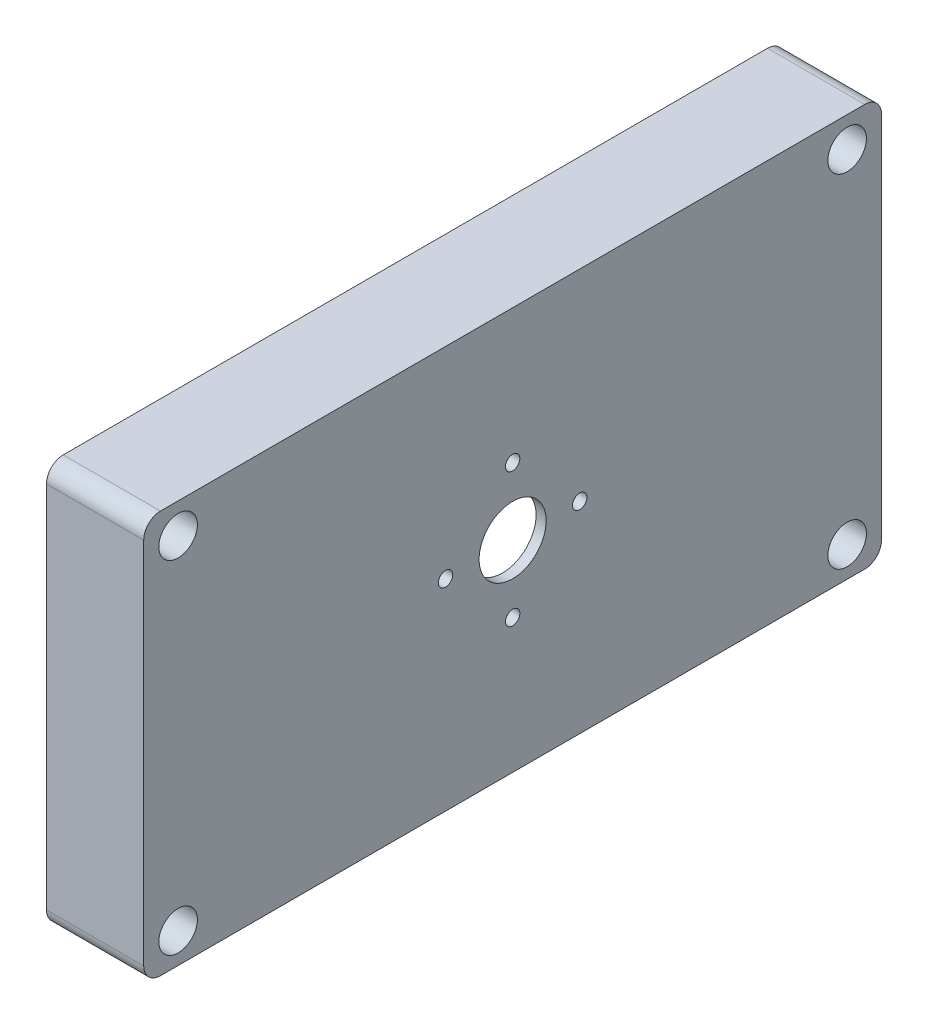
SolidWorks part; units mm, degrees
material "ألمنيوم خلائطي"
ref_plane "Front" through (0, 0, 0) normal (0, 0, 1) x (1, 0, 0)
ref_plane "Top" through (0, 0, 0) normal (0, 1, 0) x (1, 0, 0)
ref_plane "Right" through (0, 0, 0) normal (1, 0, 0) x (0, 0, -1)
sketch "Sketch1" plane through (0, 0, 0) normal (1, 0, 0) x (0, 0, -1)
  line L1 (110, 60) -> (-110, 60)
  line L2 (110, 60) -> (110, -60)
  line L3 (110, -60) -> (-110, -60)
  line L4 (-110, 60) -> (-110, -60)
  line L5 (110, 60) -> (-110, -60) construction
  line L6 (110, -60) -> (-110, 60) construction
  point P0 (0, 0)
  dimension "D1" = 120
  dimension "D2" = 220
extrude "Boss-Extrude1" add sketch "Sketch1" along normal mid plane 29
sketch "Sketch2" plane through (-14.5, 0, 0) normal (-1, 0, 0) x (0, 0, 1)
  line L0 (-87.25, 53.4) -> (87.25, 53.4)
  line L1 (87.25, 53.4) -> (87.25, 35.9)
  line L2 (87.25, 35.9) -> (103.4, 18.75)
  line L3 (103.4, 18.75) -> (103.4, -18.75)
  line L4 (-103.4, 18.75) -> (-103.4, -18.75)
  line L5 (-87.25, 35.9) -> (-103.4, 18.75)
  line L6 (-87.25, 53.4) -> (-87.25, 35.9)
  line L7 (87.25, -35.9) -> (103.4, -18.75)
  line L8 (87.25, -53.4) -> (87.25, -35.9)
  line L9 (-87.25, -53.4) -> (87.25, -53.4)
  line L10 (-87.25, -53.4) -> (-87.25, -35.9)
  line L11 (-87.25, -35.9) -> (-103.4, -18.75)
  line L12 (0, 0) -> (0, 60) construction
  line L13 (-110, 60) -> (110, 60) construction
  line L14 (0, 0) -> (110, 0) construction
  line L15 (110, 60) -> (110, -60) construction
  point P10 (0, 53.4)
  point P11 (103.4, 0)
  point P23 (-103.4, 0)
  dimension "D1" = 87.25
  dimension "D2" = 17.5
  dimension "D3" = 6.6
  dimension "D4" = 18.75
  dimension "D5" = 6.6
extrude "Cut-Extrude1" cut sketch "Sketch2" against normal blind 26
fillet "Fillet1" radius 1 8 edges at (-1.5, 18.75, -103.4) (-1.5, -18.75, -103.4) (-1.5, -53.4, -87.25) (-1.5, -53.4, 87.25) (-1.5, -18.75, 103.4) (-1.5, 18.75, 103.4) (-1.5, 53.4, 87.25) (-1.5, 53.4, -87.25)
fillet "Fillet2" radius 10 4 edges at (-1.5, -35.9, -87.25) (-1.5, -35.9, 87.25) (-1.5, 35.9, 87.25) (-1.5, 35.9, -87.25)
sketch "Sketch3" plane through (-14.5, 0, 0) normal (-1, 0, 0) x (0, 0, 1)
  line L24 (-89.25, 52.4) -> (-89.25, 39.8674)
  line L25 (-91.4259, 34.3828) -> (-104.584, 20.41)
  line L26 (-105.4, 18.3533) -> (-105.4, -18.3533)
  line L27 (-104.584, -20.41) -> (-91.4259, -34.3828)
  line L28 (-89.25, -39.8674) -> (-89.25, -52.4)
  line L29 (-86.25, -55.4) -> (86.25, -55.4)
  line L30 (89.25, -52.4) -> (89.25, -39.8674)
  line L31 (91.4259, -34.3828) -> (104.584, -20.41)
  line L32 (105.4, -18.3533) -> (105.4, 18.3533)
  line L33 (104.584, 20.41) -> (91.4259, 34.3828)
  line L34 (89.25, 39.8674) -> (89.25, 52.4)
  line L35 (86.25, 55.4) -> (-86.25, 55.4)
  line L36 (-89.25, 52.4) -> (-89.25, 39.8674)
  line L37 (-91.4259, 34.3828) -> (-104.584, 20.41)
  line L38 (-105.4, 18.3533) -> (-105.4, -18.3533)
  line L39 (-104.584, -20.41) -> (-91.4259, -34.3828)
  line L40 (-89.25, -39.8674) -> (-89.25, -52.4)
  line L41 (-86.25, -55.4) -> (86.25, -55.4)
  line L42 (89.25, -52.4) -> (89.25, -39.8674)
  line L43 (91.4259, -34.3828) -> (104.584, -20.41)
  line L44 (105.4, -18.3533) -> (105.4, 18.3533)
  line L45 (104.584, 20.41) -> (91.4259, 34.3828)
  line L46 (89.25, 39.8674) -> (89.25, 52.4)
  line L47 (86.25, 55.4) -> (-86.25, 55.4)
  line L48 (-87.25, 52.4) -> (-87.25, 39.8674)
  line L49 (-89.9699, 33.0117) -> (-103.128, 19.0388)
  line L50 (-103.4, 18.3533) -> (-103.4, -18.3533)
  line L51 (-103.128, -19.0388) -> (-89.9699, -33.0117)
  line L52 (-87.25, -39.8674) -> (-87.25, -52.4)
  line L53 (-86.25, -53.4) -> (86.25, -53.4)
  line L54 (87.25, -52.4) -> (87.25, -39.8674)
  line L55 (89.9699, -33.0117) -> (103.128, -19.0388)
  line L56 (103.4, -18.3533) -> (103.4, 18.3533)
  line L57 (103.128, 19.0388) -> (89.9699, 33.0117)
  line L58 (87.25, 39.8674) -> (87.25, 52.4)
  line L59 (86.25, 53.4) -> (-86.25, 53.4)
  line L60 (-87.25, 52.4) -> (-87.25, 39.8674)
  line L61 (-89.9699, 33.0117) -> (-103.128, 19.0388)
  line L62 (-103.4, 18.3533) -> (-103.4, -18.3533)
  line L63 (-103.128, -19.0388) -> (-89.9699, -33.0117)
  line L64 (-87.25, -39.8674) -> (-87.25, -52.4)
  line L65 (-86.25, -53.4) -> (86.25, -53.4)
  line L66 (87.25, -52.4) -> (87.25, -39.8674)
  line L67 (89.9699, -33.0117) -> (103.128, -19.0388)
  line L68 (103.4, -18.3533) -> (103.4, 18.3533)
  line L69 (103.128, 19.0388) -> (89.9699, 33.0117)
  line L70 (87.25, 39.8674) -> (87.25, 52.4)
  line L71 (86.25, 53.4) -> (-86.25, 53.4)
  line L72 (86.25, 58.2) -> (-86.25, 58.2)
  line L73 (-92.05, 52.4) -> (-92.05, 39.8674)
  line L74 (-93.4643, 36.3024) -> (-106.6225, 22.3295)
  line L75 (-108.2, 18.3533) -> (-108.2, -18.3533)
  line L76 (-106.6225, -22.3295) -> (-93.4643, -36.3024)
  line L77 (-92.05, -39.8674) -> (-92.05, -52.4)
  line L78 (-86.25, -58.2) -> (86.25, -58.2)
  line L79 (92.05, -52.4) -> (92.05, -39.8674)
  line L80 (93.4643, -36.3024) -> (106.6225, -22.3295)
  line L81 (108.2, -18.3533) -> (108.2, 18.3533)
  line L82 (106.6225, 22.3295) -> (93.4643, 36.3024)
  line L83 (92.05, 39.8674) -> (92.05, 52.4)
  arc A24 (-91.4259, 34.3828) -> (-89.25, 39.8674) centre (-97.25, 39.8674) ccw
  arc A25 (-104.584, 20.41) -> (-105.4, 18.3533) centre (-102.4, 18.3533) ccw
  arc A26 (-105.4, -18.3533) -> (-104.584, -20.41) centre (-102.4, -18.3533) ccw
  arc A27 (-89.25, -39.8674) -> (-91.4259, -34.3828) centre (-97.25, -39.8674) ccw
  arc A28 (-89.25, -52.4) -> (-86.25, -55.4) centre (-86.25, -52.4) ccw
  arc A29 (86.25, -55.4) -> (89.25, -52.4) centre (86.25, -52.4) ccw
  arc A30 (91.4259, -34.3828) -> (89.25, -39.8674) centre (97.25, -39.8674) ccw
  arc A31 (104.584, -20.41) -> (105.4, -18.3533) centre (102.4, -18.3533) ccw
  arc A32 (105.4, 18.3533) -> (104.584, 20.41) centre (102.4, 18.3533) ccw
  arc A33 (89.25, 39.8674) -> (91.4259, 34.3828) centre (97.25, 39.8674) ccw
  arc A34 (89.25, 52.4) -> (86.25, 55.4) centre (86.25, 52.4) ccw
  arc A35 (-86.25, 55.4) -> (-89.25, 52.4) centre (-86.25, 52.4) ccw
  arc A36 (-91.4259, 34.3828) -> (-89.25, 39.8674) centre (-97.25, 39.8674) ccw
  arc A37 (-104.584, 20.41) -> (-105.4, 18.3533) centre (-102.4, 18.3533) ccw
  arc A38 (-105.4, -18.3533) -> (-104.584, -20.41) centre (-102.4, -18.3533) ccw
  arc A39 (-89.25, -39.8674) -> (-91.4259, -34.3828) centre (-97.25, -39.8674) ccw
  arc A40 (-89.25, -52.4) -> (-86.25, -55.4) centre (-86.25, -52.4) ccw
  arc A41 (86.25, -55.4) -> (89.25, -52.4) centre (86.25, -52.4) ccw
  arc A42 (91.4259, -34.3828) -> (89.25, -39.8674) centre (97.25, -39.8674) ccw
  arc A43 (104.584, -20.41) -> (105.4, -18.3533) centre (102.4, -18.3533) ccw
  arc A44 (105.4, 18.3533) -> (104.584, 20.41) centre (102.4, 18.3533) ccw
  arc A45 (89.25, 39.8674) -> (91.4259, 34.3828) centre (97.25, 39.8674) ccw
  arc A46 (89.25, 52.4) -> (86.25, 55.4) centre (86.25, 52.4) ccw
  arc A47 (-86.25, 55.4) -> (-89.25, 52.4) centre (-86.25, 52.4) ccw
  arc A48 (-89.9699, 33.0117) -> (-87.25, 39.8674) centre (-97.25, 39.8674) ccw
  arc A49 (-103.128, 19.0388) -> (-103.4, 18.3533) centre (-102.4, 18.3533) ccw
  arc A50 (-103.4, -18.3533) -> (-103.128, -19.0388) centre (-102.4, -18.3533) ccw
  arc A51 (-87.25, -39.8674) -> (-89.9699, -33.0117) centre (-97.25, -39.8674) ccw
  arc A52 (-87.25, -52.4) -> (-86.25, -53.4) centre (-86.25, -52.4) ccw
  arc A53 (86.25, -53.4) -> (87.25, -52.4) centre (86.25, -52.4) ccw
  arc A54 (89.9699, -33.0117) -> (87.25, -39.8674) centre (97.25, -39.8674) ccw
  arc A55 (103.128, -19.0388) -> (103.4, -18.3533) centre (102.4, -18.3533) ccw
  arc A56 (103.4, 18.3533) -> (103.128, 19.0388) centre (102.4, 18.3533) ccw
  arc A57 (87.25, 39.8674) -> (89.9699, 33.0117) centre (97.25, 39.8674) ccw
  arc A58 (87.25, 52.4) -> (86.25, 53.4) centre (86.25, 52.4) ccw
  arc A59 (-86.25, 53.4) -> (-87.25, 52.4) centre (-86.25, 52.4) ccw
  arc A60 (-89.9699, 33.0117) -> (-87.25, 39.8674) centre (-97.25, 39.8674) ccw
  arc A61 (-103.128, 19.0388) -> (-103.4, 18.3533) centre (-102.4, 18.3533) ccw
  arc A62 (-103.4, -18.3533) -> (-103.128, -19.0388) centre (-102.4, -18.3533) ccw
  arc A63 (-87.25, -39.8674) -> (-89.9699, -33.0117) centre (-97.25, -39.8674) ccw
  arc A64 (-87.25, -52.4) -> (-86.25, -53.4) centre (-86.25, -52.4) ccw
  arc A65 (86.25, -53.4) -> (87.25, -52.4) centre (86.25, -52.4) ccw
  arc A66 (89.9699, -33.0117) -> (87.25, -39.8674) centre (97.25, -39.8674) ccw
  arc A67 (103.128, -19.0388) -> (103.4, -18.3533) centre (102.4, -18.3533) ccw
  arc A68 (103.4, 18.3533) -> (103.128, 19.0388) centre (102.4, 18.3533) ccw
  arc A69 (87.25, 39.8674) -> (89.9699, 33.0117) centre (97.25, 39.8674) ccw
  arc A70 (87.25, 52.4) -> (86.25, 53.4) centre (86.25, 52.4) ccw
  arc A71 (-86.25, 53.4) -> (-87.25, 52.4) centre (-86.25, 52.4) ccw
  arc A72 (-86.25, 58.2) -> (-92.05, 52.4) centre (-86.25, 52.4) ccw
  arc A73 (-93.4643, 36.3024) -> (-92.05, 39.8674) centre (-97.25, 39.8674) ccw
  arc A74 (-106.6225, 22.3295) -> (-108.2, 18.3533) centre (-102.4, 18.3533) ccw
  arc A75 (-108.2, -18.3533) -> (-106.6225, -22.3295) centre (-102.4, -18.3533) ccw
  arc A76 (-92.05, -39.8674) -> (-93.4643, -36.3024) centre (-97.25, -39.8674) ccw
  arc A77 (-92.05, -52.4) -> (-86.25, -58.2) centre (-86.25, -52.4) ccw
  arc A78 (86.25, -58.2) -> (92.05, -52.4) centre (86.25, -52.4) ccw
  arc A79 (93.4643, -36.3024) -> (92.05, -39.8674) centre (97.25, -39.8674) ccw
  arc A80 (106.6225, -22.3295) -> (108.2, -18.3533) centre (102.4, -18.3533) ccw
  arc A81 (108.2, 18.3533) -> (106.6225, 22.3295) centre (102.4, 18.3533) ccw
  arc A82 (92.05, 39.8674) -> (93.4643, 36.3024) centre (97.25, 39.8674) ccw
  arc A83 (92.05, 52.4) -> (86.25, 58.2) centre (86.25, 52.4) ccw
  dimension "D1" = 2
  dimension "D2" = 0
  dimension "D3" = 2.8
extrude "Cut-Extrude3" cut sketch "Sketch3" against normal blind 3 contours L83 A83 L72 A72 L73 A73 L74 A74 L75 A75 L76 A76 L77 A77 L78 A78 L79 A79 L80 A80 L81 A81 L82 A82 A47 L47 A46 L46 A45 L45 A44 L44 A43 L43 A42 L42 A41 L41 A40 L40 A39 L39 A38 L38 A37 L37 A36 L36
hole_wizard "CBORE for M4 Cheese Head Screw1" positions "Sketch7" profile "Sketch6" counterbore size "M4" standard "ISO" end condition up to next
sketch "Sketch7" plane through (14.5, 0, 0) normal (1, 0, 0) x (0, 0, -1)
  line L0 (0, 0) -> (0, 60) construction
  line L1 (110, 60) -> (-110, 60) construction
  line L3 (0, 0) -> (110, 0) construction
  line L4 (110, -60) -> (110, 60) construction
  point P0 (99.75, 51)
  point P2 (-99.75, 51)
  point P4 (-99.75, -51)
  point P6 (99.75, -51)
  dimension "D1" = 102
  dimension "D2" = 199.5
sketch "Sketch6" plane through (14.5, 51, -99.75) normal (0, 1, 0) x (0, 0, -1)
  line L0 (0, 0) -> (0, 29)
  line L1 (0, 29) -> (2.4, 29)
  line L3 (2.4, 29) -> (2.4, 20)
  line L4 (2.4, 20) -> (5.75, 20)
  line L5 (5.75, 20) -> (5.75, 0)
  line L7 (5.75, 0) -> (0, 0)
  line L11 (0, -6.35) -> (0, 107.95) construction
  dimension "Thru Hole Dia." = 4.8
  dimension "Thru Hole Depth" = 29
  dimension "C'Bore Dia." = 11.5
  dimension "C'Bore Depth" = 20
fillet "Fillet3" radius 5 4 edges at (0, 60, 110) (0, -60, 110) (0, -60, -110) (0, 60, -110)
sketch "Sketch8" plane through (-14.5, 0, 0) normal (-1, 0, 0) x (0, 0, 1)
  line L0 (0, 0) -> (0, 60) construction
  line L1 (-105, 60) -> (105, 60) construction
  line L2 (0, 0) -> (110, 0) construction
  line L3 (110, 55) -> (110, -55) construction
  circle A0 centre (99.75, 38.25) radius 4.5
  circle A1 centre (99.75, -38.25) radius 4.5
  circle A2 centre (99.75, 51) radius 2.4 construction
  circle A3 centre (99.75, 51) radius 2.4
  circle A4 centre (-99.75, -38.25) radius 4.5
  circle A5 centre (-99.75, 38.25) radius 4.5
  dimension "D1" = 9
  dimension "D2" = 76.5
extrude "Cut-Extrude4" cut sketch "Sketch8" against normal blind 10 contours A0 | A1 | A4 | A5
sketch "Sketch9" plane through (14.5, 0, 0) normal (1, 0, 0) x (0, 0, -1)
  circle A0 centre (0, 0) radius 10
  dimension "D1" = 20
extrude "Cut-Extrude5" cut sketch "Sketch9" against normal up to next
hole_wizard "M4 Clearance Hole1" positions "Sketch11" profile "Sketch10" hole size "M4" standard "ISO" end condition up to next
sketch "Sketch11" plane through (14.5, 0, 0) normal (1, 0, 0) x (0, 0, -1)
  line L0 (0, 0) -> (0, 20) construction
  point P0 (0, 20)
  dimension "D1" = 20
sketch "Sketch10" plane through (14.5, 20, 0) normal (0, 1, 0) x (0, 0, -1)
  line L0 (0, 0) -> (0, 3.001)
  line L1 (0, 3.001) -> (2.15, 3.001)
  line L2 (2.15, 3.001) -> (2.15, 0)
  line L5 (2.15, 0) -> (0, 0)
  line L11 (0, -6.35) -> (0, 107.95) construction
  dimension "Thru Hole Dia." = 4.3
  dimension "Thru Hole Depth" = 3.001
pattern_circular "CirPattern1" count 4 over 360 about axis through (0, 0, 0) along (1, 0, 0) of "M4 Clearance Hole1"
